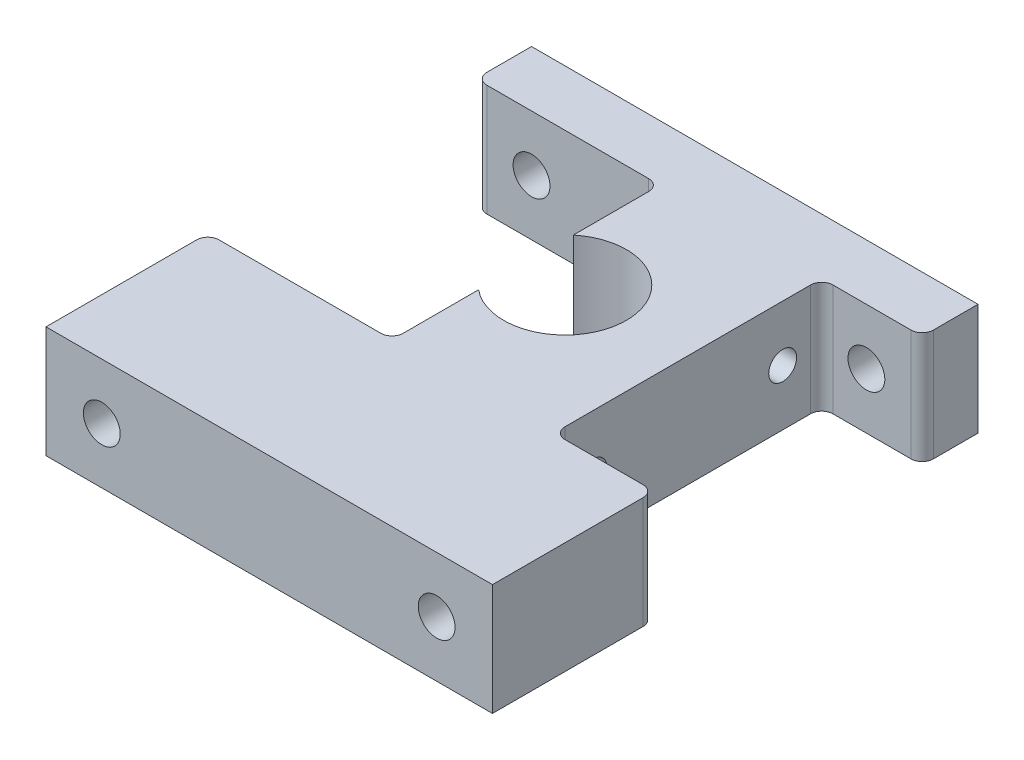
SolidWorks part; units mm, degrees
material "6061 合金"
ref_plane "前视基准面" through (0, 0, 0) normal (0, 0, 1) x (1, 0, 0)
ref_plane "上视基准面" through (0, 0, 0) normal (0, 1, 0) x (1, 0, 0)
ref_plane "右视基准面" through (0, 0, 0) normal (1, 0, 0) x (0, 0, -1)
sketch "草图1" plane through (0, 0, 0) normal (0, 1, 0) x (1, 0, 0)
  line L1 (-20, -17) -> (20, -17)
  line L2 (-20, -17) -> (-20, 17)
  line L3 (-20, 17) -> (20, 17)
  line L4 (20, -17) -> (20, 17)
  line L5 (-20, -17) -> (20, 17) construction
  line L6 (-20, 17) -> (20, -17) construction
  circle A0 centre (0, 0) radius 5.5
  dimension "D1" = 11
  dimension "D2" = 34
  dimension "D3" = 40
extrude "凸台-拉伸1" add sketch "草图1" along normal blind 10
sketch "草图3" plane through (0, 0, 0) normal (0, -1, 0) x (1, 0, 0)
  line L0 (-20, -17) -> (-20, 17) construction
  line L1 (-36.5, -12) -> (-4.5, -12)
  line L2 (-36.5, -12) -> (-36.5, 12)
  line L3 (-36.5, 12) -> (-4.5, 12)
  line L4 (-3.5, -11) -> (-3.5, 11)
  line L5 (-36.5, -12) -> (-3.5, 12) construction
  line L6 (-36.5, 12) -> (-3.5, -12) construction
  line L7 (20, 17) -> (20, -17) construction
  line L8 (12, -12) -> (29, -12)
  line L9 (11, -11) -> (11, 11)
  line L10 (12, 12) -> (29, 12)
  line L11 (29, -12) -> (29, 12)
  line L12 (11, -12) -> (29, 12) construction
  line L13 (11, 12) -> (29, -12) construction
  arc A0 (-4.5, -12) -> (-3.5, -11) centre (-4.5, -11) ccw
  arc A1 (-4.5, 12) -> (-3.5, 11) centre (-4.5, 11) cw
  arc A4 (12, -12) -> (11, -11) centre (12, -11) cw
  arc A5 (11, 11) -> (12, 12) centre (12, 11) cw
  point P0 (-20, 0)
  point P14 (20, 0)
  dimension "D3" = 1
  dimension "D5" = 1
  dimension "D1" = 3.5
  dimension "D2" = 24
  dimension "D4" = 9
extrude "切除-拉伸2" cut sketch "草图3" against normal through all
fillet "圆角1" radius 1 4 edges at (-20, 5, 12) (-20, 5, -12) (20, 5, 12) (20, 5, -12)
sketch "草图9" plane through (-3.5, 0, 0) normal (-1, 0, 0) x (0, 0, 1)
  line L0 (-1004.2426, 5) -> (48995.7574, 5) construction
  line L1 (-4.2426, 0) -> (-4.2426, 10) construction
  circle A0 centre (-8.5, 5) radius 1.5
  circle A1 centre (8.5, 5) radius 1.5
  point P5 (-4.2426, 5)
  dimension "D1" = 3
  dimension "D2" = 8.5
  dimension "D3" = 8.5
hole_wizard "M3 螺纹孔1" positions "草图12" profile "草图11" tap size "M3" standard "GB" end condition through all
sketch "草图12" plane through (-3.5, 0, 0) normal (-1, 0, 0) x (0, 0, 1)
  point P0 (-8.5, 5)
  point P3 (8.5, 5)
cosmetic thread "孔螺蚊线5" parameters "D2"=3
sketch "草图11" plane through (-3.5, 5, -8.5) normal (0, 1, 0) x (0, 0, 1)
  line L0 (0, 0) -> (0, 23.5)
  line L1 (0, 23.5) -> (1.25, 23.5)
  line L2 (1.25, 23.5) -> (1.25, 0)
  line L5 (1.25, 0) -> (0, 0)
  line L11 (0, -6.35) -> (0, 107.95) construction
  dimension "通孔螺纹孔钻头直径" = 2.5
  dimension "通孔螺纹孔钻头深度" = 23.5
cosmetic thread "孔螺蚊线7" parameters "D2"=3
sketch "草图13" plane through (0, 0, 0) normal (0, -1, 0) x (-1, 0, 0)
  line L0 (-20, -17) -> (-20, -13) construction
  line L1 (20, -17) -> (-20, -17)
  line L2 (20, -17) -> (20, -26.5)
  line L3 (20, -26.5) -> (-20, -26.5)
  line L4 (-20, -17) -> (-20, -26.5)
  dimension "D1" = 9.5
extrude "凸台-拉伸2" add sketch "草图13" against normal blind 10
sketch "草图14" plane through (0, 0, 26.5) normal (0, 0, 1) x (1, 0, 0)
  line L0 (0, 10) -> (0, 0) construction
  line L1 (20, 10) -> (-20, 10) construction
  line L2 (-20, 5) -> (20, 5) construction
  line L3 (-20, 10) -> (-20, 0) construction
  line L4 (20, 10) -> (20, 0) construction
  circle A0 centre (-15, 5) radius 2
  circle A1 centre (15, 5) radius 2
  dimension "D1" = 4
  dimension "D2" = 4
  dimension "D3" = 15
  dimension "D4" = 15
hole_wizard "M4 螺纹孔1" positions "草图15" profile "草图16" tap size "M4" standard "GB"
sketch "草图15" plane through (0, 0, 26.5) normal (0, 0, 1) x (1, 0, 0)
  point P0 (-15, 5)
  point P3 (15, 5)
sketch "草图16" plane through (-15, 5, 26.5) normal (1, 0, 0) x (0, -1, 0)
  line L0 (0, 0) -> (0, 14.5)
  line L1 (0, 14.5) -> (1.65, 14.5)
  line L2 (1.65, 14.5) -> (1.65, 0)
  line L5 (1.65, 0) -> (0, 0)
  line L11 (0, -6.35) -> (0, 107.95) construction
  dimension "通孔螺纹孔钻头直径" = 3.3
  dimension "通孔螺纹孔钻头深度" = 14.5
cosmetic thread "孔螺蚊线8" parameters "D2"=4
cosmetic thread "孔螺蚊线9" parameters "D2"=4
sketch "草图19" plane through (0, 0, -17) normal (0, 0, -1) x (-1, 0, 0)
  line L0 (-20, 5) -> (20, 5) construction
  line L1 (20, 5) -> (0, 10) construction
  line L2 (0, 10) -> (0, 0) construction
  circle A0 centre (-15, 5) radius 2
  circle A1 centre (15, 5) radius 2
  dimension "D1" = 4
  dimension "D2" = 4
hole_wizard "M4 螺纹孔3" positions "3D草图3" profile "草图20" tap size "M4" standard "GB" end condition up to next
sketch3d "3D草图3"
  point P0 (15, 5, -17)
  point P3 (-15, 5, -17)
sketch "草图20" plane through (15, 5, -17) normal (1, 0, 0) x (0, 1, 0)
  line L0 (0, 0) -> (0, 5)
  line L1 (0, 5) -> (1.65, 5)
  line L2 (1.65, 5) -> (1.65, 0)
  line L5 (1.65, 0) -> (0, 0)
  line L11 (0, -6.35) -> (0, 107.95) construction
  dimension "通孔螺纹孔钻头直径" = 3.3
  dimension "通孔螺纹孔钻头深度" = 5
cosmetic thread "孔螺蚊线10" parameters "D2"=4
cosmetic thread "孔螺蚊线11" parameters "D2"=4
